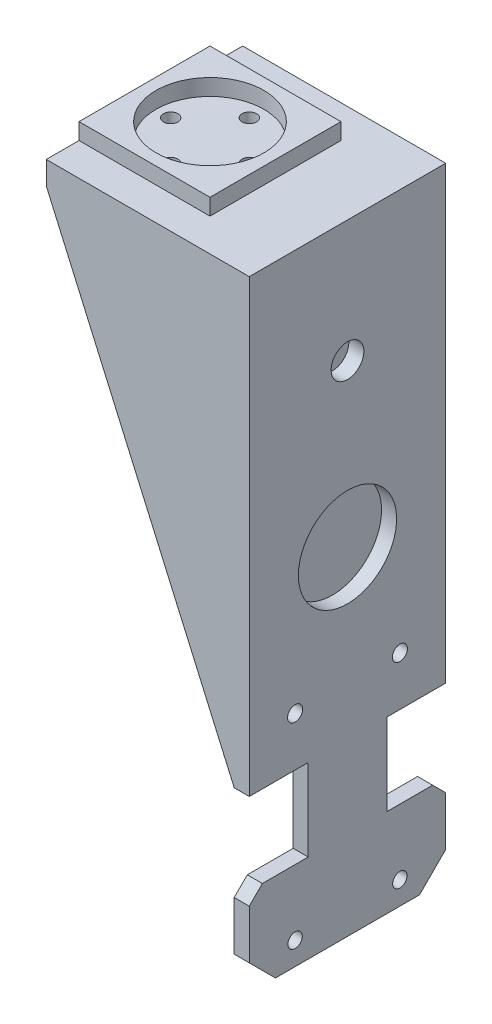
SolidWorks part; units mm, degrees
ref_plane "前视基准面" through (0, 0, 0) normal (0, 0, 1) x (1, 0, 0)
ref_plane "上视基准面" through (0, 0, 0) normal (0, 1, 0) x (1, 0, 0)
ref_plane "右视基准面" through (0, 0, 0) normal (1, 0, 0) x (0, 0, -1)
other "Configuration Table"
sketch "草图1" plane through (0, 0, 0) normal (0, 1, 0) x (1, 0, 0)
  line L1 (-15, 15) -> (15, 15)
  line L2 (-15, 15) -> (-15, -15)
  line L3 (-15, -15) -> (15, -15)
  line L4 (15, 15) -> (15, -15)
  line L5 (-15, 15) -> (15, -15) construction
  line L6 (-15, -15) -> (15, 15) construction
  point P0 (0, 0)
  dimension "D1" = 30
  dimension "D2" = 30
extrude "凸台-拉伸1" add sketch "草图1" along normal blind 86.25
sketch "草图2" plane through (0, 86.25, 0) normal (0, 1, 0) x (1, 0, 0)
  line L1 (-15, 15) -> (-15, -15) construction
  circle A0 centre (1, 0) radius 8.25
  dimension "D1" = 16.5
  dimension "D2" = 16
extrude "切除-拉伸1" cut sketch "草图2" against normal blind 2.5
sketch "草图3" plane through (0, 0, -15) normal (0, 0, -1) x (-1, 0, 0)
  line L0 (5, 0) -> (5, 66.25)
  line L1 (-15, 0) -> (15, 0) construction
  line L2 (5, 66.25) -> (15, 66.25)
  line L3 (15, 86.25) -> (15, 0) construction
  line L4 (15, 66.25) -> (15, 0)
  line L5 (15, 0) -> (5, 0)
  line L6 (-5, 86.25) -> (-5, 66.25)
  line L7 (-15, 86.25) -> (15, 86.25) construction
  line L8 (-5, 66.25) -> (-15, 66.25)
  line L9 (-15, 86.25) -> (-15, 0) construction
  line L10 (-15, 66.25) -> (-15, 86.25)
  line L11 (-15, 86.25) -> (-5, 86.25)
  dimension "D1" = 10
  dimension "D2" = 20
  dimension "D3" = 10
extrude "切除-拉伸2" cut sketch "草图3" against normal through all
sketch "草图4" plane through (0, 0, -15) normal (0, 0, -1) x (-1, 0, 0)
  line L0 (-5, 66.25) -> (-15, 66.25)
  line L1 (-5, 66.25) -> (-5, 86.25) construction
  line L2 (-5, 66.25) -> (-5, 86.25)
  line L3 (-5, 86.25) -> (-15, 86.25)
  line L4 (-15, 86.25) -> (-15, 66.25)
extrude "凸台-拉伸2" add sketch "草图4" against normal through all
sketch "草图5" plane through (0, 0, -15) normal (0, 0, -1) x (-1, 0, 0)
  line L0 (-15, 86.25) -> (15, 86.25) construction
  line L1 (-15, 0) -> (-22, 0)
  line L2 (-15, 0) -> (-15, 86.25)
  line L3 (-15, 86.25) -> (-22, 86.25)
  line L4 (-22, 0) -> (-22, 86.25)
  dimension "D1" = 7
extrude "凸台-拉伸3" add sketch "草图5" against normal through all
sketch "草图6" plane through (0, 0, 0) normal (0, -1, 0) x (1, 0, 0)
  line L4 (22, 15) -> (-5, 15)
  line L5 (-5, 15) -> (-5, -15)
  line L6 (-5, -15) -> (22, -15)
  line L7 (22, -15) -> (22, 15)
  line L8 (22, 15) -> (-5, 15)
  line L9 (-5, 15) -> (-5, -15)
  line L10 (-5, -15) -> (22, -15)
  line L11 (22, -15) -> (22, 15)
  dimension "D1" = 0
extrude "凸台-拉伸4" add sketch "草图6" along normal blind 11
sketch "草图7" plane through (-5, 0, 0) normal (-1, 0, 0) x (0, 0, 1)
  line L0 (0, -11) -> (0, 54.1271) construction
  line L1 (15, -11) -> (-15, -11) construction
  line L3 (-10.25, -11) -> (10.25, -11)
  line L4 (-10.25, -11) -> (-10.25, 25)
  line L5 (-10.25, 25) -> (10.25, 25)
  line L6 (10.25, -11) -> (10.25, 25)
  dimension "D1" = 20.5
  dimension "D2" = 36
extrude "切除-拉伸3" cut sketch "草图7" against normal offset from surface (24.7 mm away) 2.3 up to face at (22, 37.625, 0)
sketch "草图8" plane through (19.7, 0, 0) normal (-1, 0, 0) x (0, 0, 1)
  line L0 (0, -11) -> (0, 21.6816) construction
  line L1 (-10.25, -11) -> (10.25, -11) construction
  circle A0 centre (-8, -7.5) radius 1.1
  circle A1 centre (-8, 22.5) radius 1.15
  circle A2 centre (8, 22.5) radius 1.15
  circle A3 centre (8, -7.5) radius 1.1
  dimension "D3" = 2.2
  dimension "D5" = 2.3
  dimension "D1" = 30
  dimension "D2" = 3.5
  dimension "D4" = 16
extrude "切除-拉伸4" cut sketch "草图8" against normal blind 23
sketch "草图9" plane through (0, 86.25, 0) normal (0, 1, 0) x (1, 0, 0)
  circle A1 centre (1, 0) radius 8.25
  dimension "D1" = 16.5
extrude "切除-拉伸5" cut sketch "草图9" against normal blind 2.5
sketch "草图10" plane through (0, 83.75, 0) normal (0, 1, 0) x (1, 0, 0)
  line L0 (-7.25, 0) -> (9.25, 0) construction
  line L1 (1, 8.25) -> (1, -8.25) construction
  circle A0 centre (1, 0) radius 8.25 construction
  circle A1 centre (1, 0) radius 8.25 construction
  circle A2 centre (1, 6) radius 1.1
  circle A3 centre (7, 0) radius 1.1
  circle A4 centre (1, -6) radius 1.1
  circle A5 centre (-5, 0) radius 1.1
  dimension "D1" = 2.2
  dimension "D2" = 12
  dimension "D3" = 12
extrude "切除-拉伸6" cut sketch "草图10" against normal blind 10
sketch "草图11" plane through (0, 0, -15) normal (0, 0, -1) x (-1, 0, 0)
  line L0 (9, 86.25) -> (9, 80.25)
  line L1 (-22, 86.25) -> (15, 86.25) construction
  line L2 (9, 80.25) -> (-18, 80.25)
  line L3 (-18, 80.25) -> (-18, -11)
  line L4 (5, -11) -> (-22, -11) construction
  line L5 (-18, -11) -> (15, -11)
  line L6 (9, 86.25) -> (15, 86.25)
  line L7 (15, 86.25) -> (15, -11)
  line L8 (-22, 86.25) -> (-22, -11) construction
  dimension "D1" = 6
  dimension "D2" = 4
  dimension "D3" = 6
extrude "切除-拉伸7" cut sketch "草图11" against normal through all
sketch "草图12" plane through (19.7, 0, 0) normal (-1, 0, 0) x (0, 0, 1)
  line L0 (0, 0) -> (0, 95.5949) construction
  line L1 (-10.25, -11) -> (10.25, -11) construction
  line L2 (-15, 80.25) -> (-10.25, 80.25)
  line L3 (-15, 80.25) -> (-15, -11)
  line L4 (-15, -11) -> (-10.25, -11)
  line L5 (-10.25, 80.25) -> (-10.25, -11)
  line L6 (10.25, 80.25) -> (10.25, -11)
  line L7 (15, -11) -> (10.25, -11)
  line L8 (15, 80.25) -> (15, -11)
  line L9 (15, 80.25) -> (10.25, 80.25)
  dimension "D1" = 4.75
extrude "凸台-拉伸5" add sketch "草图12" along normal through all
sketch "草图14" plane through (19.7, 0, 0) normal (-1, 0, 0) x (0, 0, 1)
  line L0 (-10.25, -11) -> (-10.25, 80.25) construction
  line L1 (-10.25, 30) -> (10.25, 30)
  line L2 (-10.25, 30) -> (-10.25, 25)
  line L3 (-10.25, 25) -> (10.25, 25)
  line L4 (10.25, 30) -> (10.25, 25)
  line L5 (10.25, 80.25) -> (10.25, -11) construction
  line L6 (-10.25, -11) -> (10.25, -11) construction
  dimension "D1" = 5
  dimension "D2" = 36
extrude "凸台-拉伸6" add sketch "草图14" along normal through all
sketch "草图13" plane through (0, 0, -15) normal (0, 0, -1) x (-1, 0, 0)
  line L0 (9, 80.25) -> (-19.7, 15)
  line L1 (9, 86.25) -> (9, -11) construction
  line L2 (-19.7, 15) -> (-19.7, -11)
  line L3 (9, -11) -> (-22, -11) construction
  line L4 (-19.7, -8.6) -> (-19.7, -6.4) construction
  line L5 (9, 80.25) -> (9, -11)
  line L6 (9, -11) -> (-19.7, -11)
  dimension "D1" = 26
extrude "切除-拉伸9" cut sketch "草图13" against normal through all
chamfer "倒角1" distance 4 angle 45 2 edges at (20.85, -11, 15) (20.85, -11, -15)
sketch "草图15" plane through (19.7, 0, 0) normal (-1, 0, 0) x (0, 0, 1)
  circle A0 centre (0, 40.4829) radius 7.5
  circle A1 centre (0, 65.1382) radius 2.5
  dimension "D1" = 15
  dimension "D2" = 5
extrude "切除-拉伸10" cut sketch "草图15" against normal through all
sketch "草图16" plane through (19.7, 0, 0) normal (-1, 0, 0) x (0, 0, 1)
  line L0 (0, -11) -> (0, 41.2951) construction
  line L1 (-11, -11) -> (11, -11) construction
  line L2 (6, 15) -> (6, 2.5)
  line L3 (-15, 15) -> (-6, 15)
  line L4 (-15, 15) -> (-15, 2.5)
  line L5 (-15, 2.5) -> (-6, 2.5)
  line L6 (-6, 15) -> (-6, 2.5)
  line L7 (15, 2.5) -> (6, 2.5)
  line L8 (15, 15) -> (15, 2.5)
  line L9 (15, 15) -> (6, 15)
  dimension "D1" = 12.5
  dimension "D2" = 9
extrude "切除-拉伸11" cut sketch "草图16" against normal blind 10
chamfer "倒角2" distance 2 angle 45 2 edges at (20.85, 2.5, -15) (20.85, 2.5, 15)
sketch "草图18" plane through (0, 86.25, 0) normal (0, 1, 0) x (1, 0, 0)
  line L8 (-9, 10) -> (-9, -10)
  line L9 (-9, -10) -> (11, -10)
  line L10 (11, -10) -> (11, 10)
  line L11 (11, 10) -> (-9, 10)
  circle A0 centre (1, 0) radius 8.25 construction
  circle A1 centre (1, 0) radius 8.25
  point P8 (1, 0)
  dimension "D2" = 10
  dimension "D1" = 10
  dimension "D3" = 10
extrude "切除-拉伸12" cut sketch "草图18" against normal up to surface (2.5 mm away) flip side to cut contours L11 L8 L9 L10 up to face at (1, 83.75, -4.9)
